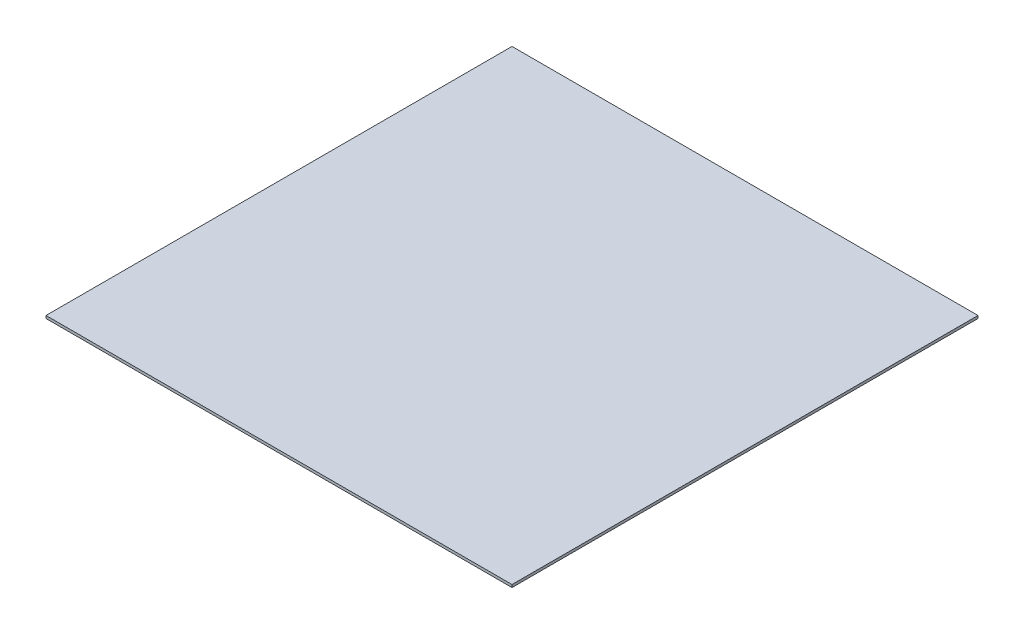
SolidWorks part; units mm, degrees
ref_plane "Front Plane" through (0, 0, 0) normal (0, 0, 1) x (1, 0, 0)
ref_plane "Top Plane" through (0, 0, 0) normal (0, 1, 0) x (1, 0, 0)
ref_plane "Right Plane" through (0, 0, 0) normal (1, 0, 0) x (0, 0, -1)
sketch "Sketch1" plane through (0, 0, 0) normal (0, 1, 0) x (1, 0, 0)
  line L1 (0, 0) -> (22.352, 0)
  line L2 (0, 0) -> (0, 22.352)
  line L3 (0, 22.352) -> (22.352, 22.352)
  line L4 (22.352, 0) -> (22.352, 22.352)
extrude "Boss-Extrude1" add sketch "Sketch1" along normal blind 0.127 contours L1 L4 L3 L2
